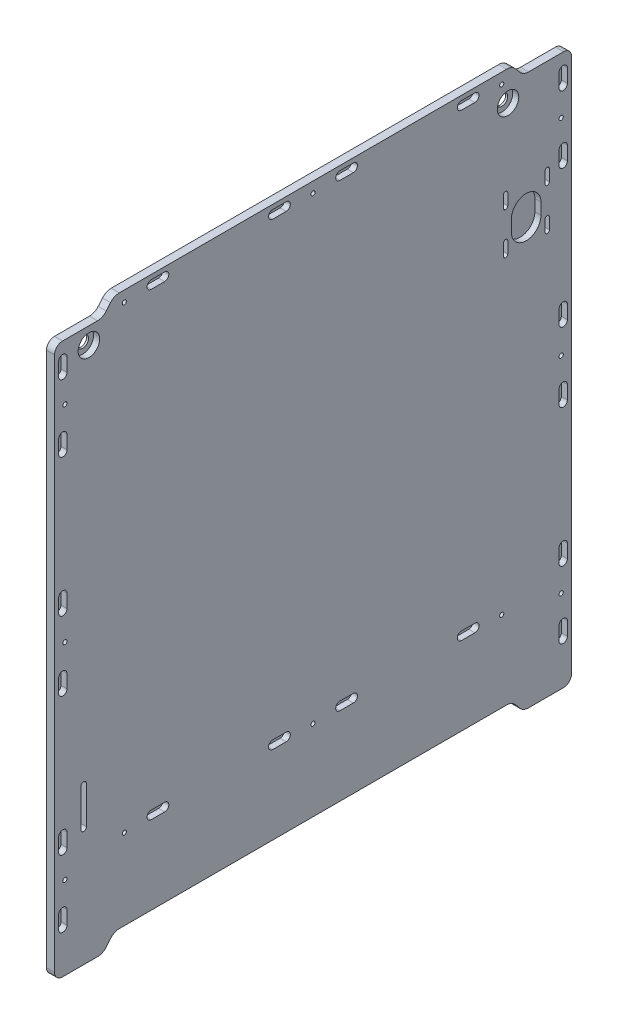
SolidWorks part; units mm, degrees
ref_plane "Alzado" through (0, 0, 0) normal (0, 0, 1) x (1, 0, 0)
ref_plane "Planta" through (0, 0, 0) normal (0, 1, 0) x (1, 0, 0)
ref_plane "Vista lateral" through (0, 0, 0) normal (1, 0, 0) x (0, 0, -1)
sketch "Croquis1" plane through (0, 0, 0) normal (1, 0, 0) x (0, 0, -1)
  line L0 (-15.4032, 213.9092) -> (-15.4032, -196.0905) construction
  line L1 (138.549, -203.0545) -> (135.2533, -199.1268)
  line L2 (171.0968, -206.0908) -> (145.0604, -206.0908)
  line L3 (177.0968, 198.0069) -> (177.0968, -200.0908)
  line L4 (145.0968, 204.0069) -> (171.0968, 204.0069)
  line L5 (-159.667, 213.9092) -> (128.8605, 213.9092)
  line L6 (-166.1784, 210.8729) -> (-169.3918, 207.0432)
  line L7 (-175.9032, 204.0069) -> (-201.9032, 204.0069)
  line L8 (-207.9032, 198.0069) -> (-207.9032, -200.0908)
  line L9 (-201.9032, -206.0908) -> (-175.8668, -206.0908)
  line L10 (-169.3555, -203.0545) -> (-166.0597, -199.1268)
  line L11 (-159.5483, -196.0905) -> (128.7419, -196.0905)
  line L12 (135.3719, 210.8729) -> (138.5854, 207.0432)
  line L13 (126.3968, 133.9092) -> (126.3968, 125.4092)
  line L14 (129.5968, 133.9092) -> (129.5968, 125.4092)
  line L15 (157.3968, 133.9092) -> (157.3968, 125.4092)
  line L16 (160.5968, 133.9092) -> (160.5968, 125.4092)
  line L17 (157.3968, 102.9092) -> (157.3968, 94.4092)
  line L18 (160.5968, 102.9092) -> (160.5968, 94.4092)
  line L19 (126.3968, 102.9092) -> (126.3968, 94.4092)
  line L20 (129.5968, 102.9092) -> (129.5968, 94.4092)
  line L21 (-207.9032, 8.9094) -> (177.0968, 8.9094) construction
  line L22 (-207.9032, -1.0419) -> (177.0968, -1.0419) construction
  arc A0 (128.7419, -196.0905) -> (135.2533, -199.1268) centre (128.7419, -204.5905) cw
  arc A1 (145.0604, -206.0908) -> (138.549, -203.0545) centre (145.0604, -197.5908) cw
  arc A2 (177.0968, -200.0908) -> (171.0968, -206.0908) centre (171.0968, -200.0908) cw
  arc A3 (171.0968, 204.0069) -> (177.0968, 198.0069) centre (171.0968, 198.0069) cw
  arc A4 (145.0968, 204.0069) -> (138.5854, 207.0432) centre (145.0968, 212.5069) cw
  arc A5 (-159.667, 213.9092) -> (-166.1784, 210.8729) centre (-159.667, 205.4092) ccw
  arc A6 (-175.9032, 204.0069) -> (-169.3918, 207.0432) centre (-175.9032, 212.5069) ccw
  arc A7 (-201.9032, 204.0069) -> (-207.9032, 198.0069) centre (-201.9032, 198.0069) ccw
  arc A8 (-207.9032, -200.0908) -> (-201.9032, -206.0908) centre (-201.9032, -200.0908) ccw
  arc A9 (-175.8668, -206.0908) -> (-169.3555, -203.0545) centre (-175.8668, -197.5908) ccw
  arc A10 (-159.5483, -196.0905) -> (-166.0597, -199.1268) centre (-159.5483, -204.5905) ccw
  arc A11 (128.8605, 213.9092) -> (135.3719, 210.8729) centre (128.8605, 205.4092) cw
  circle A12 centre (-182.3032, 191.5069) radius 4.25
  circle A13 centre (129.7968, 191.5069) radius 4.25
  arc A14 (129.5968, 133.9092) -> (126.3968, 133.9092) centre (127.9968, 133.9092) ccw
  arc A15 (126.3968, 125.4092) -> (129.5968, 125.4092) centre (127.9968, 125.4092) ccw
  arc A16 (160.5968, 133.9092) -> (157.3968, 133.9092) centre (158.9968, 133.9092) ccw
  arc A17 (157.3968, 125.4092) -> (160.5968, 125.4092) centre (158.9968, 125.4092) ccw
  arc A18 (160.5968, 102.9092) -> (157.3968, 102.9092) centre (158.9968, 102.9092) ccw
  arc A19 (157.3968, 94.4092) -> (160.5968, 94.4092) centre (158.9968, 94.4092) ccw
  arc A20 (129.5968, 102.9092) -> (126.3968, 102.9092) centre (127.9968, 102.9092) ccw
  arc A21 (126.3968, 94.4092) -> (129.5968, 94.4092) centre (127.9968, 94.4092) ccw
  circle A22 centre (-15.4032, 205.9092) radius 1.55
  circle A23 centre (125.0968, 205.9092) radius 1.55
  circle A24 centre (-155.9032, 205.9092) radius 1.55
  circle A25 centre (-15.4032, -136.0908) radius 1.55
  circle A26 centre (125.0968, -136.0908) radius 1.55
  circle A27 centre (-155.9032, -136.0908) radius 1.55
  circle A28 centre (-200.1532, 162.2069) radius 1.6
  circle A29 centre (-200.1532, 8.9094) radius 1.6
  circle A30 centre (-200.1532, -144.3882) radius 1.6
  circle A31 centre (169.3468, -144.3882) radius 1.6
  circle A32 centre (169.3468, 8.9094) radius 1.6
  circle A33 centre (169.3468, 162.2069) radius 1.6
  point P94 (-15.4032, 8.9094)
  point P95 (-15.4032, 8.9094)
  dimension "D3" = 15.9023
  dimension "D5" = 25.6
  dimension "D6" = 8.5
  dimension "D8" = 1.8
  dimension "D10" = 2
  dimension "D4" = 9.9513
  dimension "D2" = 47.3
  dimension "D7" = 80
  dimension "D12" = 41.8
  dimension "D13" = 52
  dimension "D14" = 52
  dimension "D15" = 7.75
  dimension "D16" = 52
  dimension "D17" = 52
  dimension "D22" = 6
  dimension "D23" = 6
  dimension "D24" = 8.5
  dimension "D25" = 8.5
  dimension "D26" = 8.5
  dimension "D27" = 50
  dimension "D29" = 8.5
  dimension "D30" = 8.5
  dimension "D33" = 3.2
  dimension "D34" = 3.2
  dimension "D11" = 2
  dimension "D18" = 7.75
  dimension "D20" = 9.9023
  dimension "D21" = 10.0003
  dimension "D28" = 32.0364
  dimension "D31" = 32
  dimension "D32" = 50
extrude "Saliente-Extruir1" add sketch "Croquis1" along normal blind 6
sketch "Croquis3" plane through (6, 0, 0) normal (1, 0, 0) x (0, 0, -1)
  line L0 (-15.4032, 213.9092) -> (-15.4032, -196.0905) construction
  line L1 (128.8605, 213.9092) -> (-159.667, 213.9092) construction
  line L2 (-159.5483, -196.0905) -> (128.7419, -196.0905) construction
  line L3 (132.2968, 115.5069) -> (132.2968, 107.0069)
  line L4 (154.2968, 115.5069) -> (154.2968, 107.0069)
  line L5 (-198.6032, 192.2069) -> (-198.6032, 182.2069)
  line L6 (-204.8032, 192.2069) -> (-204.8032, 182.2069)
  line L7 (-175.9032, 204.0069) -> (-201.9032, 204.0069) construction
  line L8 (-207.9032, 198.0069) -> (-207.9032, -200.0908) construction
  line L9 (-198.6032, 142.2069) -> (-198.6032, 132.2069)
  line L10 (-204.8032, 142.2069) -> (-204.8032, 132.2069)
  line L11 (177.0968, 8.9094) -> (-207.9032, 8.9094) construction
  line L12 (177.0968, -200.0908) -> (177.0968, 198.0069) construction
  line L13 (-198.6032, -124.3882) -> (-198.6032, -114.3882)
  line L14 (-204.8032, -124.3882) -> (-204.8032, -114.3882)
  line L15 (-204.8032, -174.3882) -> (-204.8032, -164.3882)
  line L16 (-198.6032, -174.3882) -> (-198.6032, -164.3882)
  line L17 (-15.4032, 8.9094) -> (-15.4032, 213.9092) construction
  line L19 (-201.7032, 179.1069) -> (-201.7032, 145.3069) construction
  line L20 (-198.6032, 39.7671) -> (-198.6032, 29.7671)
  line L21 (-204.8032, 39.7671) -> (-204.8032, 29.7671)
  line L22 (-198.6032, -11.9484) -> (-198.6032, -21.9484)
  line L23 (-204.8032, -11.9484) -> (-204.8032, -21.9484)
  line L24 (-201.7032, 26.6671) -> (-201.7032, -8.8484) construction
  line L25 (167.7968, -174.3882) -> (167.7968, -164.3882)
  line L26 (173.9968, -174.3882) -> (173.9968, -164.3882)
  line L27 (173.9968, -124.3882) -> (173.9968, -114.3882)
  line L28 (167.7968, -124.3882) -> (167.7968, -114.3882)
  line L29 (173.9968, -11.9484) -> (173.9968, -21.9484)
  line L30 (167.7968, -11.9484) -> (167.7968, -21.9484)
  line L31 (173.9968, 39.7671) -> (173.9968, 29.7671)
  line L32 (-45.4032, 210.5092) -> (-35.4032, 210.5092)
  line L33 (-45.4032, 204.3092) -> (-35.4032, 204.3092)
  line L34 (-135.9032, 210.5092) -> (-125.9032, 210.5092)
  line L35 (-135.9032, 204.3092) -> (-125.9032, 204.3092)
  line L36 (167.7968, 39.7671) -> (167.7968, 29.7671)
  line L37 (105.0968, 204.3092) -> (95.0968, 204.3092)
  line L38 (105.0968, 210.5092) -> (95.0968, 210.5092)
  line L39 (14.5968, 204.3092) -> (4.5968, 204.3092)
  line L40 (14.5968, 210.5092) -> (4.5968, 210.5092)
  line L41 (-135.9032, -131.4908) -> (-125.9032, -131.4908)
  line L42 (-135.9032, -137.6908) -> (-125.9032, -137.6908)
  line L43 (-45.4032, -131.4908) -> (-35.4032, -131.4908)
  line L44 (-45.4032, -137.6908) -> (-35.4032, -137.6908)
  line L45 (14.5968, -131.4908) -> (4.5968, -131.4908)
  line L46 (14.5968, -137.6908) -> (4.5968, -137.6908)
  line L47 (105.0968, -131.4908) -> (95.0968, -131.4908)
  line L48 (105.0968, -137.6908) -> (95.0968, -137.6908)
  line L49 (-135.9032, 210.5092) -> (-135.9032, -131.4908) construction
  line L50 (173.9968, 142.2069) -> (173.9968, 132.2069)
  line L51 (167.7968, 142.2069) -> (167.7968, 132.2069)
  line L52 (173.9968, 192.2069) -> (173.9968, 182.2069)
  line L53 (167.7968, 192.2069) -> (167.7968, 182.2069)
  circle A0 centre (-182.3032, 191.5069) radius 8
  circle A1 centre (129.7968, 191.5069) radius 8
  arc A2 (154.2968, 115.5069) -> (132.2968, 115.5069) centre (143.2968, 115.5069) ccw
  arc A3 (132.2968, 107.0069) -> (154.2968, 107.0069) centre (143.2968, 107.0069) ccw
  arc A4 (-198.6032, 192.2069) -> (-204.8032, 192.2069) centre (-201.7032, 192.2069) ccw
  arc A5 (-204.8032, 182.2069) -> (-198.6032, 182.2069) centre (-201.7032, 182.2069) ccw
  arc A6 (-198.6032, 142.2069) -> (-204.8032, 142.2069) centre (-201.7032, 142.2069) ccw
  arc A7 (-204.8032, 132.2069) -> (-198.6032, 132.2069) centre (-201.7032, 132.2069) ccw
  arc A8 (-204.8032, -114.3882) -> (-198.6032, -114.3882) centre (-201.7032, -114.3882) cw
  arc A9 (-198.6032, -124.3882) -> (-204.8032, -124.3882) centre (-201.7032, -124.3882) cw
  arc A10 (-204.8032, -164.3882) -> (-198.6032, -164.3882) centre (-201.7032, -164.3882) cw
  arc A11 (-198.6032, -174.3882) -> (-204.8032, -174.3882) centre (-201.7032, -174.3882) cw
  arc A12 (-198.6032, 39.7671) -> (-204.8032, 39.7671) centre (-201.7032, 39.7671) ccw
  arc A13 (-204.8032, 29.7671) -> (-198.6032, 29.7671) centre (-201.7032, 29.7671) ccw
  arc A14 (-198.6032, -11.9484) -> (-204.8032, -11.9484) centre (-201.7032, -11.9484) ccw
  arc A15 (-204.8032, -21.9484) -> (-198.6032, -21.9484) centre (-201.7032, -21.9484) ccw
  arc A16 (167.7968, -174.3882) -> (173.9968, -174.3882) centre (170.8968, -174.3882) ccw
  arc A17 (173.9968, -164.3882) -> (167.7968, -164.3882) centre (170.8968, -164.3882) ccw
  arc A18 (167.7968, -124.3882) -> (173.9968, -124.3882) centre (170.8968, -124.3882) ccw
  arc A19 (173.9968, -114.3882) -> (167.7968, -114.3882) centre (170.8968, -114.3882) ccw
  arc A20 (173.9968, -21.9484) -> (167.7968, -21.9484) centre (170.8968, -21.9484) cw
  arc A21 (167.7968, -11.9484) -> (173.9968, -11.9484) centre (170.8968, -11.9484) cw
  arc A22 (173.9968, 29.7671) -> (167.7968, 29.7671) centre (170.8968, 29.7671) cw
  arc A23 (167.7968, 39.7671) -> (173.9968, 39.7671) centre (170.8968, 39.7671) cw
  arc A24 (173.9968, 132.2069) -> (167.7968, 132.2069) centre (170.8968, 132.2069) cw
  arc A25 (167.7968, 142.2069) -> (173.9968, 142.2069) centre (170.8968, 142.2069) cw
  arc A26 (173.9968, 182.2069) -> (167.7968, 182.2069) centre (170.8968, 182.2069) cw
  arc A27 (167.7968, 192.2069) -> (173.9968, 192.2069) centre (170.8968, 192.2069) cw
  arc A28 (-35.4032, 204.3092) -> (-35.4032, 210.5092) centre (-35.4032, 207.4092) ccw
  arc A29 (-45.4032, 210.5092) -> (-45.4032, 204.3092) centre (-45.4032, 207.4092) ccw
  arc A30 (-125.9032, 204.3092) -> (-125.9032, 210.5092) centre (-125.9032, 207.4092) ccw
  arc A31 (-135.9032, 210.5092) -> (-135.9032, 204.3092) centre (-135.9032, 207.4092) ccw
  arc A32 (105.0968, 210.5092) -> (105.0968, 204.3092) centre (105.0968, 207.4092) cw
  arc A33 (95.0968, 204.3092) -> (95.0968, 210.5092) centre (95.0968, 207.4092) cw
  arc A34 (14.5968, 210.5092) -> (14.5968, 204.3092) centre (14.5968, 207.4092) cw
  arc A35 (4.5968, 204.3092) -> (4.5968, 210.5092) centre (4.5968, 207.4092) cw
  arc A36 (-125.9032, -137.6908) -> (-125.9032, -131.4908) centre (-125.9032, -134.5908) ccw
  arc A37 (-135.9032, -131.4908) -> (-135.9032, -137.6908) centre (-135.9032, -134.5908) ccw
  arc A38 (-35.4032, -137.6908) -> (-35.4032, -131.4908) centre (-35.4032, -134.5908) ccw
  arc A39 (-45.4032, -131.4908) -> (-45.4032, -137.6908) centre (-45.4032, -134.5908) ccw
  arc A40 (14.5968, -131.4908) -> (14.5968, -137.6908) centre (14.5968, -134.5908) cw
  arc A41 (4.5968, -137.6908) -> (4.5968, -131.4908) centre (4.5968, -134.5908) cw
  arc A42 (105.0968, -131.4908) -> (105.0968, -137.6908) centre (105.0968, -134.5908) cw
  arc A43 (95.0968, -137.6908) -> (95.0968, -131.4908) centre (95.0968, -134.5908) cw
  circle A44 centre (-155.9032, 205.9092) radius 1.55 construction
  circle A45 centre (-155.9032, 205.9092) radius 1.55 construction
  dimension "D1" = 22
  dimension "D5" = 10
  dimension "D10" = 10
  dimension "D15" = 3.1
  dimension "D17" = 3.1
  dimension "D3" = 76
  dimension "D4" = 13.5
  dimension "D6" = 11.8
  dimension "D7" = 6.2
  dimension "D11" = 20
  dimension "D12" = 6.5
  dimension "D16" = 20
  dimension "D9" = 10
  dimension "D18" = 6.2
  dimension "D8" = 2
  dimension "D13" = 2
  dimension "D14" = 2
extrude "Cortar-Extruir1" cut sketch "Croquis3" against normal blind 4.5
chamfer "Chaflán1" distance 1.5 angle 45 12 edges at (0, 205.9092, 13.8532) (0, 205.9092, -126.6468) (0, -136.0908, -126.6468) (0, -136.0908, 13.8532) (0, -136.0908, 154.3532) (0, 162.2069, 198.5532) (0, 205.9092, 154.3532) (0, 162.2069, -167.7468) (0, 8.9094, -167.7468) (0, -144.3882, -170.9468) (0, -144.3882, 201.7532) (0, 8.9094, 198.5532)
sketch "Croquis4" plane through (0, 0, 0) normal (-1, 0, 0) x (0, 0, 1)
  line L0 (207.9032, -118.0908) -> (135.4562, -118.0908) construction
  line L1 (207.9032, 198.0069) -> (207.9032, -200.0908) construction
  line L2 (201.9032, -206.0908) -> (175.8668, -206.0908) construction
  line L3 (187.9032, -206.0908) -> (187.9032, -83.32) construction
  line L4 (189.4032, -118.0908) -> (189.4032, -109.8528) construction
  line L5 (187.9032, -119.5908) -> (190.4261, -119.5908) construction
  line L6 (186.2002, -118.0908) -> (186.2002, -90.0562) construction
  line L7 (184.1567, -118.0908) -> (184.1567, -90.0562)
  line L8 (188.2438, -118.0908) -> (188.2438, -90.0562)
  arc A0 (184.1567, -118.0908) -> (188.2438, -118.0908) centre (186.2002, -118.0908) ccw
  arc A1 (188.2438, -90.0562) -> (184.1567, -90.0562) centre (186.2002, -90.0562) ccw
  point P4 (188.885, -206.0908)
  point P15 (186.2002, -104.0735)
  dimension "D1" = 88
  dimension "D2" = 20
  dimension "D3" = 1.5
  dimension "D4" = 4.0872
  dimension "D5" = 28.0346
extrude "Cortar-Extruir2" cut sketch "Croquis4" against normal blind 6
equation "\"Ancho_panel\"= 385'Ancho del panel"
equation "\"Alto_panel\"= 420'Alto del panel izquierdo"
equation "\"Altura_base_taladros\"= 70'Alto taladros de la base eje Z"
equation "\"Altura_superior_taladros\"= 8mm'Distancia taladros a top"
equation "\"Distancia_vert_entre_horizontales_ensambles\"= \"Alto_panel\" - \"Altura_base_taladros\" - \"Altura_superior_taladros\"'Distancia vertical entre horizontales de ensambles"
equation "\"Latrales_separacion_barras_a_escalon_bajo\"= 12.5'Separación entre las barras y el escalón inferior de la parte superior"
equation "\"Espacio_tensor_correa_motor\"= 8.5mm'Espacio para mover el motor en vertical y tensar la correa"
